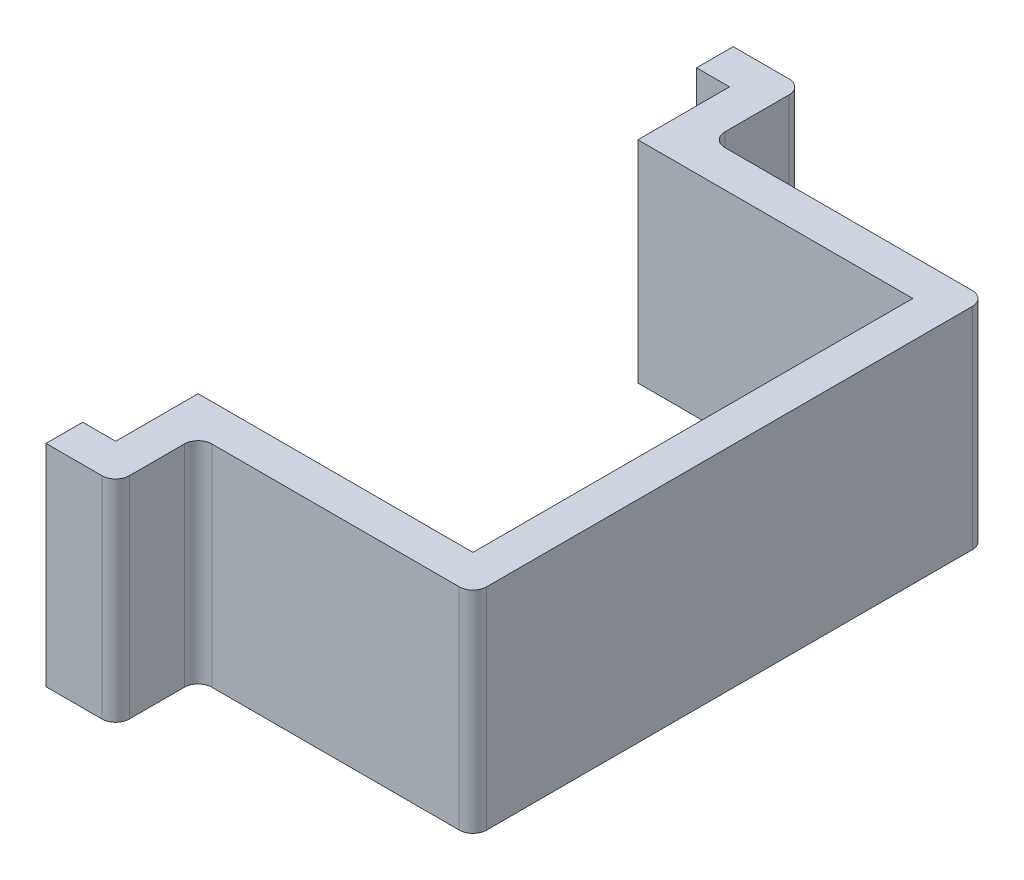
SolidWorks part; units mm, degrees
ref_plane "Front Plane" through (0, 0, 0) normal (0, 0, 1) x (1, 0, 0)
ref_plane "Top Plane" through (0, 0, 0) normal (0, 1, 0) x (1, 0, 0)
ref_plane "Right Plane" through (0, 0, 0) normal (1, 0, 0) x (0, 0, -1)
sketch "Sketch1" plane through (0, 0, 0) normal (0, 1, 0) x (1, 0, 0)
  line L0 (3.35, 28) -> (3.35, 23)
  line L9 (0, 0) -> (3.35, 0)
  line L10 (0, 0) -> (0, 23)
  line L11 (0, 23) -> (3.35, 23)
  line L12 (19.65, 0) -> (19.65, 23)
  line L14 (4.65, 0) -> (4.65, -5)
  line L15 (4.65, -5) -> (3.35, -5)
  line L16 (3.35, 0) -> (3.35, -5)
  line L17 (4.65, -5) -> (3.35, -5)
  line L18 (4.65, -5) -> (4.65, 28) construction
  line L19 (4.65, 28) -> (3.35, 28)
  line L20 (3.35, -5) -> (3.35, 28) construction
  line L21 (4.65, 28) -> (4.65, 23)
  line L22 (4.65, 0) -> (19.65, 0)
  line L23 (4.65, 23) -> (19.65, 23)
  line L24 (2.85, 28) -> (2.85, 23.5)
  line L25 (-0.5, 23.5) -> (2.85, 23.5)
  line L26 (-0.5, -0.5) -> (-0.5, 23.5)
  line L27 (-0.5, -0.5) -> (2.85, -0.5)
  line L28 (2.85, -0.5) -> (2.85, -5)
  line L29 (5.15, -0.5) -> (5.15, -5)
  line L30 (5.15, -0.5) -> (20.15, -0.5)
  line L31 (20.15, -0.5) -> (20.15, 23.5)
  line L32 (5.15, 23.5) -> (20.15, 23.5)
  line L33 (5.15, 28) -> (5.15, 23.5)
  line L34 (4.65, -4.5) -> (3.35, -4.5)
  line L35 (4.65, -4.5) -> (3.35, -4.5)
  line L37 (5.15, -5) -> (5.15, 28)
  line L38 (3.85, -5) -> (3.85, 28)
  line L39 (2.85, -5) -> (3.35, -5)
  line L40 (5.15, -5) -> (4.65, -5)
  line L41 (3.35, 28) -> (5.15, 28)
  line L42 (4.65, 28) -> (3.35, 28)
  line L43 (5.15, 28) -> (5.15, 28.5)
  line L46 (2.85, 28) -> (2.85, 28.5)
  line L47 (2.85, 28.5) -> (5.15, 28.5)
  line L48 (5.15, 28) -> (5.15, 28.5)
  dimension "D1" = 23
  dimension "D2" = 19.65
  dimension "D3" = 15
  dimension "D4" = 1.3
  dimension "D5" = 5
  dimension "D6" = 5
  dimension "D7" = 0.5
sketch "Sketch3" plane through (0, 0, 0) normal (0, 1, 0) x (1, 0, 0)
  line L1 (3.35, -5) -> (7.15, -5)
  line L2 (3.35, -5) -> (3.35, 28)
  line L3 (3.35, 28) -> (7.15, 28)
  line L4 (7.15, -5) -> (7.15, -2.5)
  line L5 (4.65, 28) -> (3.35, 28) construction
  line L6 (7.15, 25.5) -> (7.15, 28)
  line L7 (4.65, -5) -> (3.35, -5) construction
  line L8 (7.15, 25.5) -> (22.15, 25.5)
  line L10 (7.15, -2.5) -> (22.15, -2.5)
  line L11 (22.15, 25.5) -> (22.15, -2.5)
  line L12 (4.65, 23) -> (19.65, 23) construction
  line L13 (19.65, 0) -> (19.65, 23) construction
  line L14 (4.65, 0) -> (19.65, 0) construction
  line L15 (4.65, 0) -> (4.65, -5) construction
  point P20 (7.15, -3.75)
  dimension "D1" = 2.5
  dimension "D2" = 2.5
  dimension "D3" = 2.5
  dimension "D4" = 2.5
sketch "Sketch9" plane through (0, 0, 0) normal (0, 1, 0) x (1, 0, 0)
  line L0 (3.35, 28) -> (3.35, 23)
  line L9 (0, 0) -> (3.35, 0)
  line L10 (0, 0) -> (0, 23)
  line L11 (0, 23) -> (3.35, 23)
  line L12 (19.65, 0) -> (19.65, 23)
  line L14 (4.65, 0) -> (4.65, -4.5)
  line L15 (4.65, -5) -> (3.35, -5)
  line L16 (3.35, 0) -> (3.35, -4.5)
  line L17 (4.65, -5) -> (3.35, -5)
  line L18 (4.65, -4.5) -> (4.65, 28) construction
  line L19 (4.65, 28) -> (3.35, 28)
  line L20 (3.35, -4.5) -> (3.35, 28) construction
  line L21 (4.65, 28) -> (4.65, 23)
  line L22 (4.65, 0) -> (19.65, 0)
  line L23 (4.65, 23) -> (19.65, 23)
  line L24 (4.65, 28) -> (3.35, 28)
  line L25 (5.15, -5) -> (3.35, -5)
  line L26 (7.15, -5) -> (7.15, -6.25)
  line L27 (6.4, -7) -> (3.35, -7)
  line L28 (3.35, -5) -> (3.35, -7)
  line L29 (5.15, -0.5) -> (5.15, -5)
  line L30 (5.15, -0.5) -> (20.15, -0.5)
  line L31 (20.15, -0.5) -> (20.15, 23.5)
  line L32 (5.15, 23.5) -> (20.15, 23.5)
  line L33 (5.15, 28) -> (5.15, 23.5)
  line L34 (4.65, -4.5) -> (3.35, -4.5)
  line L35 (4.65, -4.5) -> (3.35, -4.5)
  line L36 (7.15, 28) -> (7.15, 26.25)
  line L37 (5.15, -5) -> (5.15, -0.5)
  line L38 (3.35, -5) -> (3.35, -7)
  line L40 (5.15, -5) -> (4.65, -5)
  line L41 (3.35, 28) -> (4.65, 28)
  line L42 (4.65, 28) -> (3.35, 28)
  line L43 (5.15, 28) -> (5.15, 28.5)
  line L47 (3.35, 30.5) -> (5.15, 30.5)
  line L48 (5.15, 28) -> (5.15, 28.5)
  line L49 (7.9, 25.5) -> (21.4, 25.5)
  line L50 (22.15, -1.75) -> (22.15, 24.75)
  line L51 (7.9, -2.5) -> (21.4, -2.5)
  line L52 (7.15, -3.25) -> (7.15, -5)
  line L53 (5.15, 23.5) -> (5.15, 28)
  line L54 (7.15, 28) -> (7.15, 29.75)
  line L55 (6.4, 30.5) -> (3.35, 30.5)
  line L57 (5.15, -5) -> (5.15, 28) construction
  line L58 (7.15, -2.5) -> (22.15, -2.5) construction
  line L60 (3.35, 30.5) -> (5.15, 30.5)
  line L61 (3.35, 30.5) -> (3.35, 28.5)
  line L62 (3.35, 28.5) -> (5.15, 28.5)
  line L64 (4.65, 0) -> (4.65, -5) construction
  line L65 (4.65, -5) -> (4.65, 28) construction
  line L66 (7.15, -2.5) -> (7.15, -5) construction
  line L67 (7.15, 28) -> (7.15, 25.5) construction
  line L68 (7.15, 25.5) -> (22.15, 25.5) construction
  line L69 (22.15, -2.5) -> (22.15, 25.5) construction
  arc A0 (7.9, -2.5) -> (7.15, -3.25) centre (7.9, -3.25) ccw
  arc A1 (7.15, 26.25) -> (7.9, 25.5) centre (7.9, 26.25) ccw
  arc A2 (7.15, 29.75) -> (6.4, 30.5) centre (6.4, 29.75) ccw
  arc A3 (21.4, 25.5) -> (22.15, 24.75) centre (21.4, 24.75) cw
  arc A4 (22.15, -1.75) -> (21.4, -2.5) centre (21.4, -1.75) cw
  arc A5 (7.15, -6.25) -> (6.4, -7) centre (6.4, -6.25) cw
  dimension "D10" = 0.75
  dimension "D1" = 23
  dimension "D2" = 19.65
  dimension "D3" = 15
  dimension "D4" = 1.3
  dimension "D5" = 5
  dimension "D6" = 5
  dimension "D7" = 0.5
  dimension "D8" = 2.5
  dimension "D9" = 2
  dimension "D11" = 0.5
extrude "Bracket" add sketch "Sketch9" along normal blind 11.5 contours L61 L62 L43 L33 L32 L31 L30 L29 L25 L15 L28 L27 L26 L52 L51 L50 L49 L36 L54 L55 L47
sketch "Sketch10" plane through (0, 0, 0) normal (0, 1, 0) x (1, 0, 0)
  line L11 (-7.0005, 30.5) -> (7.15, 30.5)
  line L13 (7.15, 30.5) -> (7.15, 25.5)
  line L20 (7.15, 25.5) -> (22.15, 25.5)
  line L21 (22.15, 25.5) -> (22.15, -2.5)
  line L22 (22.15, -2.5) -> (7.15, -2.5)
  line L23 (7.15, -2.5) -> (7.15, -7)
  line L24 (7.15, -7) -> (3.35, -7)
  line L25 (3.35, -7) -> (-14.9932, 10.7312)
  arc A12 (-7.0005, 30.5) -> (-14.9932, 10.7312) centre (-7.0005, 18.9998) ccw
  point P1 (0, 0)
  point P8 (-7.0005, 18.9998)
  point P12 (0, 0)
  point P15 (-7.0005, 30.5)
  point P32 (22.15, 25.5)
  point P37 (7.15, 30.5)
sketch "Sketch12" plane through (0, 0, 0) normal (0, 1, 0) x (1, 0, 0)
  circle A0 centre (-7, 19) radius 12
